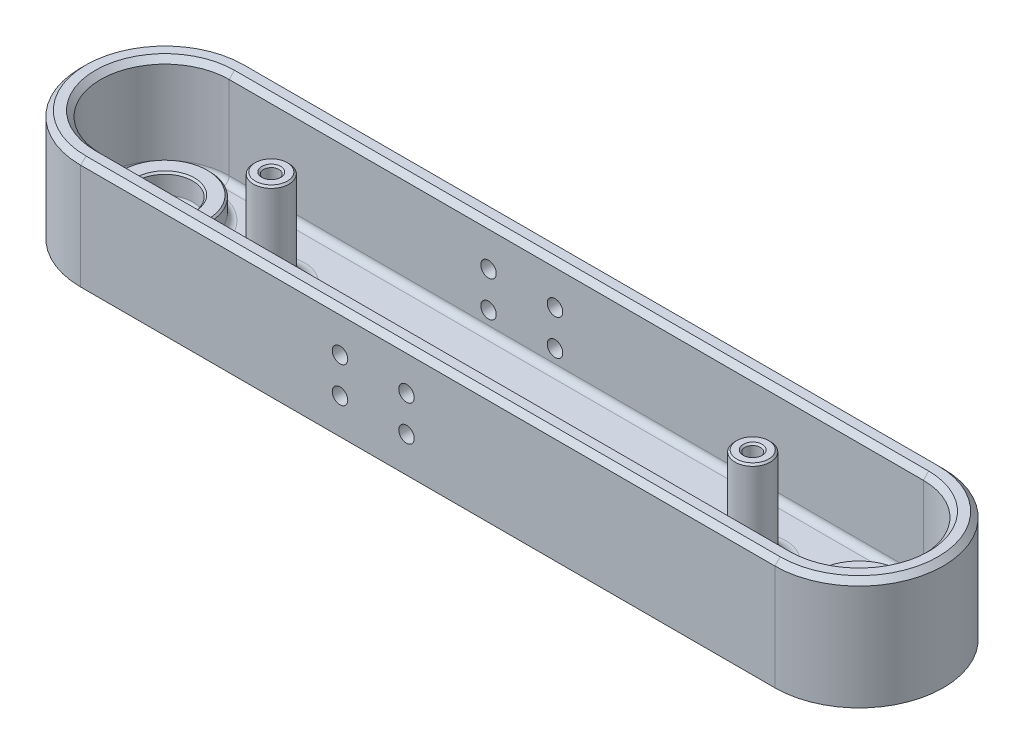
SolidWorks part; units mm, degrees
material "PLA"
ref_plane "Front Plane" through (0, 0, 0) normal (0, 0, 1) x (1, 0, 0)
ref_plane "Top Plane" through (0, 0, 0) normal (0, 1, 0) x (1, 0, 0)
ref_plane "Right Plane" through (0, 0, 0) normal (1, 0, 0) x (0, 0, -1)
sketch "Sketch1" plane through (0, 0, 0) normal (0, 1, 0) x (1, 0, 0)
  line L0 (-99.441, 0) -> (99.441, 0) construction
  line L1 (0, -55.9739) -> (0, 55.9739) construction
  line L2 (-99.441, 24.13) -> (99.441, 24.13)
  line L3 (-99.441, -24.13) -> (99.441, -24.13)
  arc A0 (-99.441, 24.13) -> (-99.441, -24.13) centre (-99.441, 0) ccw
  arc A1 (99.441, 24.13) -> (99.441, -24.13) centre (99.441, 0) cw
  point P4 (0, 0)
  point P10 (0, 0)
  dimension "D2" = 48.26
  dimension "D1" = 198.882
extrude "MainBlock" add sketch "Sketch1" along normal blind 31.75
sketch "Sketch2" plane through (0, 31.75, 0) normal (0, 1, 0) x (1, 0, 0)
  line L0 (0, 0) -> (155.7407, 0) construction
  line L1 (0, 0) -> (0, 57.4416) construction
  line L2 (-99.441, -24.13) -> (99.441, -24.13) construction
  line L3 (99.441, 24.13) -> (-99.441, 24.13) construction
  line L4 (-99.441, -24.13) -> (99.441, -24.13) construction
  line L5 (99.441, 24.13) -> (-99.441, 24.13) construction
  line L6 (-99.441, 18.415) -> (99.441, 18.415)
  line L7 (-99.441, -18.415) -> (99.441, -18.415)
  arc A0 (99.441, -24.13) -> (99.441, 24.13) centre (99.441, 0) ccw construction
  arc A1 (-99.441, 24.13) -> (-99.441, -24.13) centre (-99.441, 0) ccw construction
  arc A2 (99.441, -24.13) -> (99.441, 24.13) centre (99.441, 0) ccw construction
  arc A3 (-99.441, 24.13) -> (-99.441, -24.13) centre (-99.441, 0) ccw construction
  arc A4 (-99.441, 18.415) -> (-99.441, -18.415) centre (-99.441, 0) ccw
  arc A5 (99.441, 18.415) -> (99.441, -18.415) centre (99.441, 0) cw
  point P18 (0, 18.415)
  point P19 (0, -18.415)
  dimension "D1" = 5.715
extrude "MainPocket" cut sketch "Sketch2" against normal offset from surface (27.305 mm away) 4.445 up to face at (0, 0, 0)
sketch "Sketch3" plane through (0, 0, 0) normal (0, -1, 0) x (1, 0, 0)
  line L2 (-99.441, -24.13) -> (99.441, -24.13)
  line L3 (99.441, 24.13) -> (-99.441, 24.13)
  line L4 (-99.441, -24.13) -> (99.441, -24.13) construction
  line L5 (99.441, 24.13) -> (-99.441, 24.13) construction
  circle A0 centre (-99.441, 0) radius 4.445
  circle A1 centre (99.441, 0) radius 4.445
  arc A2 (-99.441, 24.13) -> (-99.441, -24.13) centre (-99.441, 0) ccw
  arc A3 (99.441, -24.13) -> (99.441, 24.13) centre (99.441, 0) ccw
  arc A4 (-99.441, 24.13) -> (-99.441, -24.13) centre (-99.441, 0) ccw construction
  arc A5 (99.441, -24.13) -> (99.441, 24.13) centre (99.441, 0) ccw construction
  dimension "D2" = 8.89
  dimension "D3" = 8.89
  dimension "D1" = 0
extrude "Cut-Extrude1" cut sketch "Sketch3" against normal through all
sketch "Sketch4" plane through (0, 4.445, 0) normal (0, 1, 0) x (1, 0, 0)
  line L0 (0, 0) -> (50000, 0) construction
  line L1 (0, 0) -> (0, 50000) construction
  line L2 (99.441, 18.415) -> (-99.441, 18.415)
  line L3 (-99.441, -18.415) -> (99.441, -18.415)
  line L4 (99.441, 18.415) -> (-99.441, 18.415) construction
  line L5 (-99.441, -18.415) -> (99.441, -18.415) construction
  circle A0 centre (-99.441, 0) radius 7.9566
  circle A1 centre (-99.441, 0) radius 12.7
  arc A2 (99.441, -18.415) -> (99.441, 18.415) centre (99.441, 0) ccw
  arc A3 (-99.441, 18.415) -> (-99.441, -18.415) centre (-99.441, 0) ccw
  arc A4 (99.441, -18.415) -> (99.441, 18.415) centre (99.441, 0) ccw construction
  arc A5 (-99.441, 18.415) -> (-99.441, -18.415) centre (-99.441, 0) ccw construction
  circle A6 centre (99.441, 0) radius 12.7
  circle A7 centre (99.441, 0) radius 7.9566
  dimension "D2" = 15.9131
  dimension "D3" = 25.4
  dimension "D1" = 0
extrude "Boss-Extrude1" add sketch "Sketch4" along normal blind 6.35
sketch "Sketch5" plane through (0, 0, 0) normal (0, -1, 0) x (1, 0, 0)
  line L0 (0, 0) -> (0, 50000) construction
  line L2 (-99.441, -24.13) -> (99.441, -24.13)
  line L3 (99.441, 24.13) -> (-99.441, 24.13)
  line L4 (-99.441, -24.13) -> (99.441, -24.13) construction
  line L5 (99.441, 24.13) -> (-99.441, 24.13) construction
  circle A0 centre (-99.441, 0) radius 6.35
  circle A1 centre (-99.441, 0) radius 4.445 construction
  arc A2 (-99.441, 24.13) -> (-99.441, -24.13) centre (-99.441, 0) ccw
  arc A3 (99.441, -24.13) -> (99.441, 24.13) centre (99.441, 0) ccw
  arc A4 (-99.441, 24.13) -> (-99.441, -24.13) centre (-99.441, 0) ccw construction
  arc A5 (99.441, -24.13) -> (99.441, 24.13) centre (99.441, 0) ccw construction
  circle A6 centre (-99.441, 0) radius 4.445
  circle A7 centre (99.441, 0) radius 4.445 construction
  circle A8 centre (99.441, 0) radius 6.35 construction
  dimension "D2" = 12.7
  dimension "D1" = 0
extrude "Boss-Extrude2" [suppressed] add sketch "Sketch5" along normal blind 3.81
fillet "Fillet1" [suppressed] radius 1.27
sketch "Sketch7" plane through (0, 4.445, 0) normal (0, 1, 0) x (1, 0, 0)
  line L0 (1.3556, 0) -> (50001.3556, 0) construction
  circle A0 centre (0, 0) radius 2.2225 construction
  circle A1 centre (-68.961, 0) radius 2.2225
  circle A2 centre (-99.441, 0) radius 4.445 construction
  circle A3 centre (99.441, 0) radius 4.445 construction
  circle A4 centre (99.441, 0) radius 4.445 construction
  circle A5 centre (-99.441, 0) radius 4.445 construction
  circle A6 centre (68.961, 0) radius 2.2225
  circle A7 centre (-68.961, 0) radius 5.08
  circle A8 centre (0, 0) radius 5.08 construction
  circle A9 centre (68.961, 0) radius 5.08
  dimension "D3" = 4.445
  dimension "D4" = 4.445
  dimension "D5" = 4.445
  dimension "D6" = 10.16
  dimension "D7" = 10.16
  dimension "D8" = 10.16
  dimension "D1" = 30.48
  dimension "D2" = 30.48
extrude "Boss-Extrude3" add sketch "Sketch7" along normal up to surface (27.305 mm away) up to face at (0, 31.75, 0)
fillet "Fillet2" radius 0.635 2 edges at (99.441, 4.445, 7.9566) (-99.441, 4.445, 7.9566)
fillet "Fillet3" radius 1.905 6 edges at (117.856, 4.445, 0) (0, 4.445, 18.415) (-117.856, 4.445, 0) (99.441, 4.445, -12.7) (-99.441, 4.445, 12.7) (0, 4.445, -18.415)
fillet "Fillet6" radius 4.445 2 edges at (68.961, 4.445, 5.08) (-68.961, 4.445, 5.08)
sketch "Sketch9" plane through (0, 0, 0) normal (0, -1, 0) x (1, 0, 0)
  circle A0 centre (99.441, 0) radius 4.445 construction
  circle A1 centre (99.441, 0) radius 4.445
  circle A6 centre (99.441, 0) radius 5.715
  dimension "D2" = 11.43
extrude "Bearing-Spacer" [suppressed] add sketch "Sketch9" along normal blind 8.89
fillet "Fillet7" [suppressed] radius 2.54
chamfer "Chamfer1" [suppressed] distance 0.508 angle 45
chamfer "Chamfer2" distance 0.508 angle 45 10 edges at (68.961, 31.75, 2.2225) (99.441, 4.445, 4.445) (99.441, 10.795, -12.7) (99.441, 10.795, -7.9566) (-99.441, 4.445, 4.445) (-99.441, 10.795, 12.7) (-68.961, 31.75, 5.08) (68.961, 31.75, 5.08) (-99.441, 10.795, 7.9566) (-68.961, 31.75, 2.2225)
sketch "Sketch12" plane through (0, 0, 0) normal (0, 1, 0) x (1, 0, 0)
  line L0 (-34.671, 24.13) -> (-24.511, 35.56)
  line L1 (99.441, 24.13) -> (-99.441, 24.13) construction
  line L2 (-18.161, 29.21) -> (-18.161, 24.13) construction
  line L3 (-24.511, 35.56) -> (-11.811, 35.56)
  line L4 (-34.671, 24.13) -> (-1.651, 24.13)
  line L5 (-1.651, 24.13) -> (-11.811, 35.56)
  circle A0 centre (-18.161, 29.21) radius 2.0066
  circle A1 centre (-99.441, 0) radius 4.445 construction
  point P9 (-18.161, 35.56)
  dimension "D5" = 4.0132
  dimension "D1" = 33.02
  dimension "D2" = 12.7
  dimension "D3" = 29.21
  dimension "D4" = 11.43
  dimension "D6" = 81.28
extrude "Stab_bar_Mount" [suppressed] add sketch "Sketch12" along normal blind 25.4
chamfer "Chamfer3" distance 1.524 angle 45 8 edges at (0, 31.75, -24.13) (-123.571, 31.75, 0) (123.571, 31.75, 0) (0, 31.75, 24.13) (0, 31.75, -18.415) (-117.856, 31.75, 0) (117.856, 31.75, 0) (0, 31.75, 18.415)
chamfer "Chamfer5" [suppressed] distance 0.381 angle 45
sketch "Sketch10" plane through (0, 4.445, 0) normal (0, 1, 0) x (1, 0, 0)
  circle A0 centre (68.961, 0) radius 2.2225 construction
  circle A2 centre (-68.961, 0) radius 2.2225 construction
  circle A3 centre (68.961, 0) radius 2.2225
  circle A4 centre (0, 0) radius 2.2225 construction
  circle A5 centre (-68.961, 0) radius 2.2225
extrude "Boss-Extrude4" add sketch "Sketch10" along normal blind 16.51
fillet "Fillet8" [suppressed] radius 5.08
sketch "Sketch13" plane through (0, 0, -24.13) normal (0, 0, -1) x (-1, 0, 0)
  line L0 (6.096, 20.32) -> (25.146, 20.32) construction
  line L1 (25.146, 20.32) -> (25.146, 10.16) construction
  line L2 (25.146, 10.16) -> (6.096, 10.16) construction
  line L3 (6.096, 10.16) -> (6.096, 20.32) construction
  line L4 (15.621, 20.32) -> (15.621, 10.16) construction
  line L5 (6.096, 15.24) -> (25.146, 15.24) construction
  line L6 (-99.441, 0) -> (99.441, 0) construction
  line L7 (99.441, 30.226) -> (99.441, 0) construction
  circle A0 centre (25.146, 20.32) radius 2.2225
  circle A1 centre (6.096, 20.32) radius 2.2225
  circle A2 centre (6.096, 10.16) radius 2.2225
  circle A3 centre (25.146, 10.16) radius 2.2225
  dimension "D3" = 4.445
  dimension "D1" = 19.05
  dimension "D2" = 10.16
  dimension "D4" = 15.24
  dimension "D5" = 83.82
extrude "Stabilizer-Bar-MountHoles" cut sketch "Sketch13" against normal up to surface (42.545 mm away)
mirror "Mirror1" about plane through (0, 0, 0) normal (0, 0, 1) of "Stabilizer-Bar-MountHoles"
equation "\"D5@Sketch7\"=\"D3@Sketch7\""
equation "\"D4@Sketch7\"=\"D3@Sketch7\""
equation "\"D7@Sketch7\"=\"D6@Sketch7\""
equation "\"D8@Sketch7\"=\"D6@Sketch7\""
